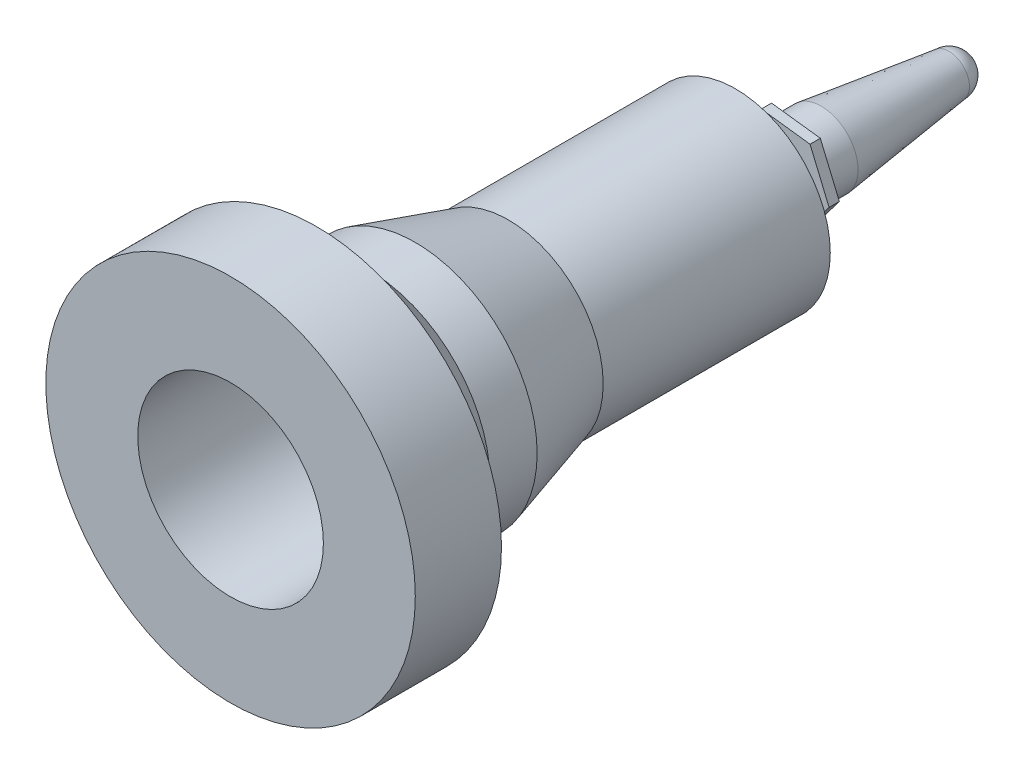
SolidWorks part; units mm, degrees
ref_plane "Front" through (0, 0, 0) normal (0, 0, 1) x (1, 0, 0)
ref_plane "Top" through (0, 0, 0) normal (0, 1, 0) x (1, 0, 0)
ref_plane "Right" through (0, 0, 0) normal (1, 0, 0) x (0, 0, -1)
sketch "Sketch2" plane through (0, 0, 0) normal (1, 0, 0) x (0, 0, -1)
  line L0 (0, 0) -> (700, 0)
  line L1 (0, 0) -> (0, 118.7369)
  line L2 (492, 24) -> (492, 92.351)
  line L3 (492, 92.351) -> (270.7367, 92.351)
  line L4 (0, 118.7369) -> (180, 118.7369)
  line L5 (180, 118.7369) -> (270.7367, 92.351)
  line L6 (700, 20) -> (575.5106, 35.8895)
  line L7 (575.5106, 35.8895) -> (545.7419, 35.8895)
  line L8 (545.7419, 35.8895) -> (545.7419, 24)
  line L9 (700, 0) -> (720, 0)
  line L10 (545.7419, 24) -> (492, 24)
  arc A0 (720, 0) -> (700, 20) centre (700, 0) ccw
  dimension "D4" = 24
  dimension "D1" = 492
  dimension "D2" = 700
  dimension "D3" = 180
revolve "Revolve1" add sketch "Sketch2" angle 360 about L0
sketch "Sketch3" plane through (0, 0, -545.7419) normal (0, 0, 1) x (1, 0, 0)
  line L1 (47.4616, -5.9464) -> (28.8805, 38.1298)
  line L2 (28.8805, 38.1298) -> (-18.5811, 44.0762)
  line L3 (-18.5811, 44.0762) -> (-47.4616, 5.9464)
  line L4 (-47.4616, 5.9464) -> (-28.8805, -38.1298)
  line L5 (-28.8805, -38.1298) -> (18.5811, -44.0762)
  line L6 (18.5811, -44.0762) -> (47.4616, -5.9464)
  circle A0 centre (0, 0) radius 41.4243 construction
extrude "Boss-Extrude1" add sketch "Sketch3" along normal blind 10
sketch "Sketch4" plane through (0, 0, 0) normal (1, 0, 0) x (0, 0, -1)
  line L0 (0, 0) -> (720, 0)
  line L1 (720, 0) -> (720, 4.2435)
  line L2 (720, 4.2435) -> (575.5106, 16.3754)
  line L3 (575.5106, 35.8895) -> (575.5106, -35.8895) construction
  line L4 (575.5106, 16.3754) -> (477.848, 16.3754)
  line L7 (477.848, 16.3754) -> (416.6518, 69.2455)
  line L8 (416.6518, 69.2455) -> (270.7367, 69.2455)
  line L9 (270.7367, 92.351) -> (270.7367, -92.351) construction
  line L10 (270.7367, 69.2455) -> (179.731, 90.448)
  line L11 (0, 90.448) -> (179.731, 90.448)
  line L12 (0, 0) -> (0, 90.448)
  arc A0 (700, -20) -> (700, 20) centre (700, 0) ccw construction
revolve "Cut-Revolve6" cut sketch "Sketch4" angle 360 about L0
sketch "Sketch5" plane through (0, 0, 0) normal (0, 0, 1) x (1, 0, 0)
  circle A0 centre (0, 0) radius 180
  circle A1 centre (0, 0) radius 90.448
  dimension "D1" = 360
extrude "Boss-Extrude2" add sketch "Sketch5" against normal blind 84
chamfer "Chamfer1" distance 50 angle 45 1 edges at (118.7369, 0, -84)
